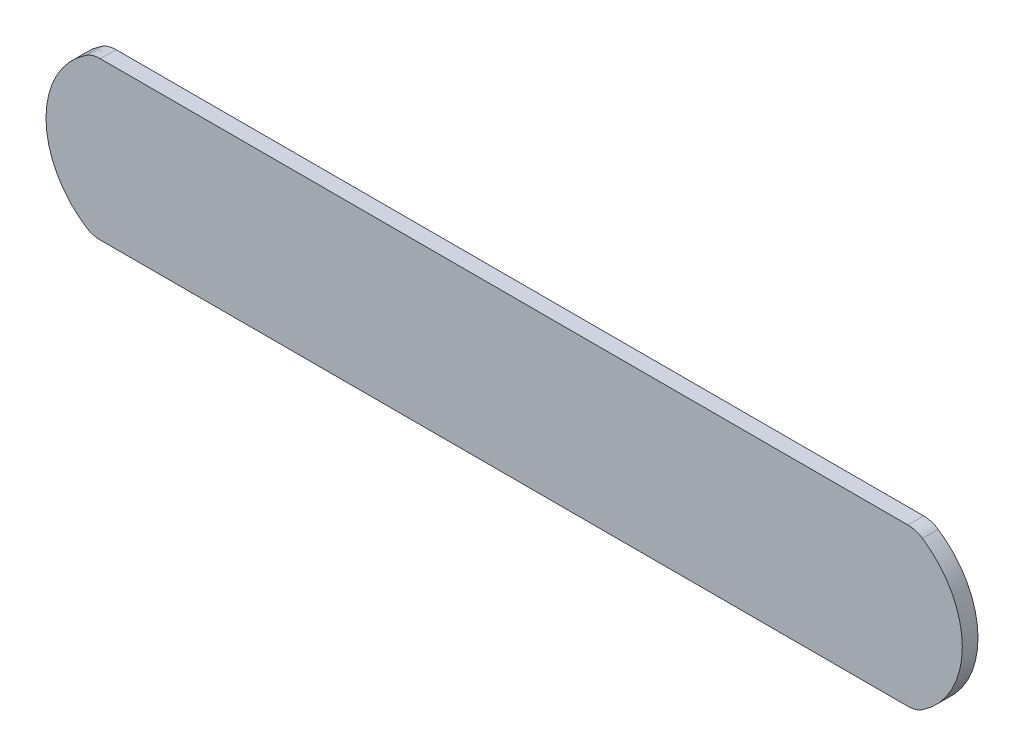
SolidWorks part; units mm, degrees
material "PMMA"
ref_plane "Alzado" through (0, 0, 0) normal (0, 0, 1) x (1, 0, 0)
ref_plane "Planta" through (0, 0, 0) normal (0, 1, 0) x (1, 0, 0)
ref_plane "Vista lateral" through (0, 0, 0) normal (1, 0, 0) x (0, 0, -1)
sketch "Croquis1" plane through (0, 0, 0) normal (0, 0, 1) x (1, 0, 0)
  line L0 (77.1341, 15) -> (-77.1341, 15)
  line L1 (-77.1341, -15) -> (77.1341, -15)
  arc A0 (-79.8961, 14.1673) -> (-79.8961, -14.1673) centre (-70.5, 0) ccw
  arc A1 (79.8961, -14.1673) -> (79.8961, 14.1673) centre (70.5, 0) ccw
  spline S0 degree 2 poles (-77.1341, 15) (-77.8713, 15) (-78.5765, 14.7873) (-79.2822, 14.5745) (-79.8961, 14.1673) knots 0 0 0 0.5 0.5 1 1 1
  spline S1 degree 2 poles (-79.8961, -14.1673) (-79.2818, -14.5748) (-78.5765, -14.7873) (-77.8707, -15) (-77.1341, -15) knots 0 0 0 0.5 0.5 1 1 1
  spline S2 degree 2 poles (77.1341, -15) (77.8713, -15) (78.5765, -14.7873) (79.2822, -14.5745) (79.8961, -14.1673) knots 0 0 0 0.5 0.5 1 1 1
  spline S3 degree 2 poles (79.8961, 14.1673) (79.2818, 14.5748) (78.5765, 14.7873) (77.8707, 15) (77.1341, 15) knots 0 0 0 0.5 0.5 1 1 1
extrude "Saliente-Extruir1" add sketch "Croquis1" along normal blind 3
